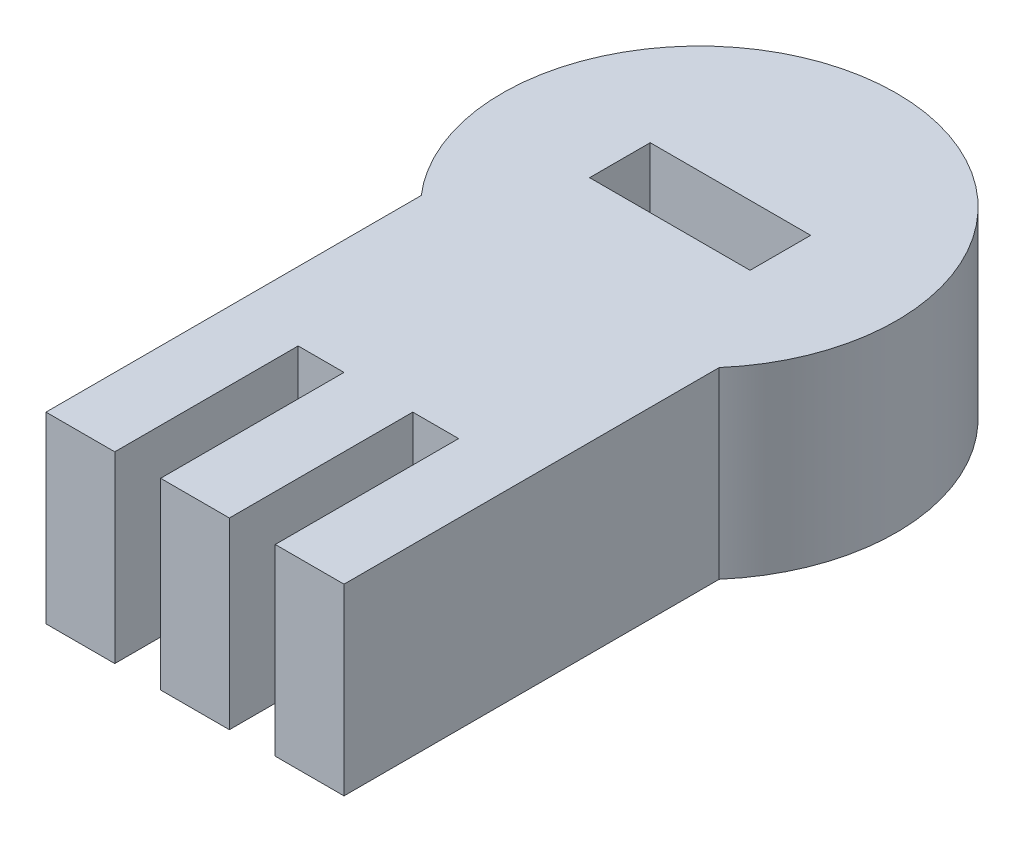
SolidWorks part; units mm, degrees
ref_plane "Front Plane" through (0, 0, 0) normal (0, 0, 1) x (1, 0, 0)
ref_plane "Top Plane" through (0, 0, 0) normal (0, 1, 0) x (1, 0, 0)
ref_plane "Right Plane" through (0, 0, 0) normal (1, 0, 0) x (0, 0, -1)
sketch "Sketch1" plane through (0, 0, 0) normal (0, 1, 0) x (1, 0, 0)
  line L0 (0, 0) -> (0, -4)
  line L1 (0, -4) -> (1.5, -4)
  line L2 (1.5, -4) -> (1.5, 0)
  line L3 (1.5, 0) -> (2.5, 0)
  line L4 (2.5, 0) -> (2.5, -4)
  line L5 (2.5, -4) -> (4, -4)
  line L6 (4, -4) -> (4, 0)
  line L7 (4, 0) -> (5, 0)
  line L8 (5, 0) -> (5, -4)
  line L9 (5, -4) -> (6.5, -4)
  line L10 (6.5, -4) -> (6.5, 0)
  line L11 (6.5, 0) -> (6.5, 4.1844)
  line L12 (1.5, 7.6789) -> (1.5, 6.3567)
  line L13 (0, 4.1844) -> (0, 0)
  line L14 (1.5, 6.3567) -> (5, 6.3567)
  line L15 (5, 6.3567) -> (5, 7.6789)
  line L16 (5, 7.6789) -> (1.5, 7.6789)
  arc A0 (6.5, 4.1844) -> (0, 4.1844) centre (3.25, 7) ccw
  dimension "D1" = 6.5
  dimension "D2" = 4
  dimension "D3" = 1
extrude "Boss-Extrude1" add sketch "Sketch1" along normal blind 4
